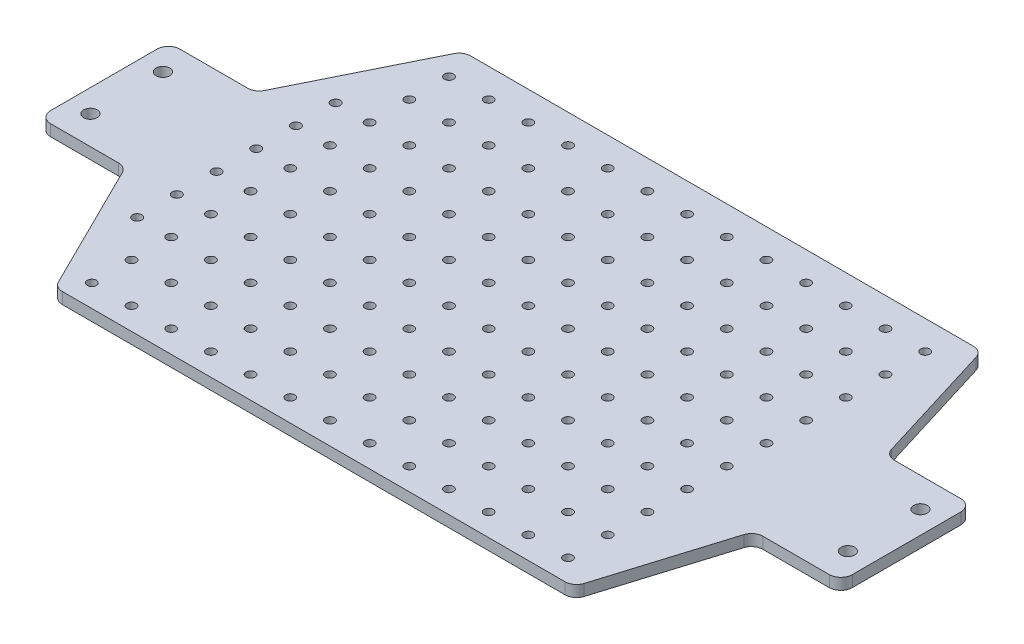
SolidWorks part; units mm, degrees
ref_plane "Front Plane" through (0, 0, 0) normal (0, 0, 1) x (1, 0, 0)
ref_plane "Top Plane" through (0, 0, 0) normal (0, 1, 0) x (1, 0, 0)
ref_plane "Right Plane" through (0, 0, 0) normal (1, 0, 0) x (0, 0, -1)
sketch "Sketch1" plane through (0, 0, 0) normal (0, 1, 0) x (1, 0, 0)
  line L0 (-217.1065, 10.4332) -> (-217.1065, -46.5668)
  line L1 (-217.1065, -46.5668) -> (-179.0065, -46.5668)
  line L2 (-179.0065, -46.5668) -> (-148.5529, -108.0668)
  line L3 (-148.5529, -108.0668) -> (80.0471, -108.0668)
  line L4 (80.0471, -108.0668) -> (98.7935, -47.0668)
  line L5 (98.7935, -47.0668) -> (136.8935, -47.0668)
  line L6 (136.8935, -47.0668) -> (136.8935, 10.9332)
  line L7 (136.8935, 10.9332) -> (98.7935, 10.9332)
  line L8 (98.7935, 10.9332) -> (80.0471, 71.9332)
  line L9 (80.0471, 71.9332) -> (-148.5529, 71.9332)
  line L10 (-148.5529, 71.9332) -> (-179.0065, 10.4332)
  line L11 (-179.0065, 10.4332) -> (-217.1065, 10.4332)
  line L12 (-148.5529, 130.6611) -> (-148.5529, -185.4725) construction
  line L13 (80.0471, 178.7683) -> (80.0471, -185.4725) construction
  dimension "D1" = 228.6
  dimension "D2" = 228.6
  dimension "D3" = 38.1
  dimension "D4" = 38.1
  dimension "D5" = 38.1
  dimension "D6" = 38.1
  dimension "D7" = 58
  dimension "D8" = 57
  dimension "D9" = 180
  dimension "D10" = 354
extrude "Boss-Extrude1" add sketch "Sketch1" along normal blind 5 contours L0 L1 L2 L3 L4 L5 L6 L7 L8 L9 L10 L11
sketch "Sketch2" plane through (0, 5, 0) normal (0, 1, 0) x (1, 0, 0)
  line L0 (-217.1065, 10.4332) -> (-217.1065, -46.5668) construction
  line L5 (-40.0685, 155.1707) -> (-40.0685, -158.002) construction
  line L6 (136.8935, -47.0668) -> (136.8935, 10.9332) construction
  circle A0 centre (-207.1065, -2.0128) radius 3
  circle A1 centre (-207.1065, -34.0128) radius 3
  circle A2 centre (126.9695, -34.0128) radius 3
  circle A3 centre (126.9695, -2.0128) radius 3
  dimension "D1" = 6
  dimension "D4" = 6
  dimension "D2" = 10
  dimension "D3" = 10
  dimension "D5" = 32
  dimension "D6" = 177.038
  dimension "D7" = 9.924
  dimension "D8" = 32
extrude "Cut-Extrude1" cut sketch "Sketch2" against normal blind 5
sketch "Sketch3" plane through (0, 5, 0) normal (0, 1, 0) x (1, 0, 0)
  line L12 (-148.5529, 71.9332) -> (-148.5529, -108.0668) construction
  line L13 (80.0471, 71.9332) -> (80.0471, -108.0668) construction
  circle A0 centre (-142.2029, 59.2332) radius 2
  circle A1 centre (-124.7029, 59.2332) radius 2
  circle A2 centre (-107.2029, 59.2332) radius 2
  circle A3 centre (-89.7029, 59.2332) radius 2
  circle A4 centre (-72.2029, 59.2332) radius 2
  circle A5 centre (-54.7029, 59.2332) radius 2
  circle A6 centre (-37.2029, 59.2332) radius 2
  circle A7 centre (-19.7029, 59.2332) radius 2
  circle A8 centre (-2.2029, 59.2332) radius 2
  circle A9 centre (15.2971, 59.2332) radius 2
  circle A10 centre (32.7971, 59.2332) radius 2
  circle A11 centre (50.2971, 59.2332) radius 2
  circle A12 centre (67.7971, 59.2332) radius 2
  circle A13 centre (-124.7029, 41.7332) radius 2
  circle A14 centre (-107.2029, 41.7332) radius 2
  circle A15 centre (-89.7029, 41.7332) radius 2
  circle A16 centre (-72.2029, 41.7332) radius 2
  circle A17 centre (-54.7029, 41.7332) radius 2
  circle A18 centre (-37.2029, 41.7332) radius 2
  circle A19 centre (-19.7029, 41.7332) radius 2
  circle A20 centre (-2.2029, 41.7332) radius 2
  circle A21 centre (15.2971, 41.7332) radius 2
  circle A22 centre (32.7971, 41.7332) radius 2
  circle A23 centre (50.2971, 41.7332) radius 2
  circle A24 centre (67.7971, 41.7332) radius 2
  circle A25 centre (-124.7029, 24.2332) radius 2
  circle A26 centre (-107.2029, 24.2332) radius 2
  circle A27 centre (-89.7029, 24.2332) radius 2
  circle A28 centre (-72.2029, 24.2332) radius 2
  circle A29 centre (-54.7029, 24.2332) radius 2
  circle A30 centre (-37.2029, 24.2332) radius 2
  circle A31 centre (-19.7029, 24.2332) radius 2
  circle A32 centre (-2.2029, 24.2332) radius 2
  circle A33 centre (15.2971, 24.2332) radius 2
  circle A34 centre (32.7971, 24.2332) radius 2
  circle A35 centre (50.2971, 24.2332) radius 2
  circle A36 centre (67.7971, 24.2332) radius 2
  circle A37 centre (-124.7029, 6.7332) radius 2
  circle A38 centre (-107.2029, 6.7332) radius 2
  circle A39 centre (-89.7029, 6.7332) radius 2
  circle A40 centre (-72.2029, 6.7332) radius 2
  circle A41 centre (-54.7029, 6.7332) radius 2
  circle A42 centre (-37.2029, 6.7332) radius 2
  circle A43 centre (-19.7029, 6.7332) radius 2
  circle A44 centre (-2.2029, 6.7332) radius 2
  circle A45 centre (15.2971, 6.7332) radius 2
  circle A46 centre (32.7971, 6.7332) radius 2
  circle A47 centre (50.2971, 6.7332) radius 2
  circle A48 centre (67.7971, 6.7332) radius 2
  circle A49 centre (-124.7029, -10.7668) radius 2
  circle A50 centre (-107.2029, -10.7668) radius 2
  circle A51 centre (-89.7029, -10.7668) radius 2
  circle A52 centre (-72.2029, -10.7668) radius 2
  circle A53 centre (-54.7029, -10.7668) radius 2
  circle A54 centre (-37.2029, -10.7668) radius 2
  circle A55 centre (-19.7029, -10.7668) radius 2
  circle A56 centre (-2.2029, -10.7668) radius 2
  circle A57 centre (15.2971, -10.7668) radius 2
  circle A58 centre (32.7971, -10.7668) radius 2
  circle A59 centre (50.2971, -10.7668) radius 2
  circle A60 centre (67.7971, -10.7668) radius 2
  circle A61 centre (-124.7029, -28.2668) radius 2
  circle A62 centre (-107.2029, -28.2668) radius 2
  circle A63 centre (-89.7029, -28.2668) radius 2
  circle A64 centre (-72.2029, -28.2668) radius 2
  circle A65 centre (-54.7029, -28.2668) radius 2
  circle A66 centre (-37.2029, -28.2668) radius 2
  circle A67 centre (-19.7029, -28.2668) radius 2
  circle A68 centre (-2.2029, -28.2668) radius 2
  circle A69 centre (15.2971, -28.2668) radius 2
  circle A70 centre (32.7971, -28.2668) radius 2
  circle A71 centre (50.2971, -28.2668) radius 2
  circle A72 centre (67.7971, -28.2668) radius 2
  circle A73 centre (-124.7029, -45.7668) radius 2
  circle A74 centre (-107.2029, -45.7668) radius 2
  circle A75 centre (-89.7029, -45.7668) radius 2
  circle A76 centre (-72.2029, -45.7668) radius 2
  circle A77 centre (-54.7029, -45.7668) radius 2
  circle A78 centre (-37.2029, -45.7668) radius 2
  circle A79 centre (-19.7029, -45.7668) radius 2
  circle A80 centre (-2.2029, -45.7668) radius 2
  circle A81 centre (15.2971, -45.7668) radius 2
  circle A82 centre (32.7971, -45.7668) radius 2
  circle A83 centre (50.2971, -45.7668) radius 2
  circle A84 centre (67.7971, -45.7668) radius 2
  circle A85 centre (-124.7029, -63.2668) radius 2
  circle A86 centre (-107.2029, -63.2668) radius 2
  circle A87 centre (-89.7029, -63.2668) radius 2
  circle A88 centre (-72.2029, -63.2668) radius 2
  circle A89 centre (-54.7029, -63.2668) radius 2
  circle A90 centre (-37.2029, -63.2668) radius 2
  circle A91 centre (-19.7029, -63.2668) radius 2
  circle A92 centre (-2.2029, -63.2668) radius 2
  circle A93 centre (15.2971, -63.2668) radius 2
  circle A94 centre (32.7971, -63.2668) radius 2
  circle A95 centre (50.2971, -63.2668) radius 2
  circle A96 centre (67.7971, -63.2668) radius 2
  circle A97 centre (-124.7029, -80.7668) radius 2
  circle A98 centre (-107.2029, -80.7668) radius 2
  circle A99 centre (-89.7029, -80.7668) radius 2
  circle A100 centre (-72.2029, -80.7668) radius 2
  circle A101 centre (-54.7029, -80.7668) radius 2
  circle A102 centre (-37.2029, -80.7668) radius 2
  circle A103 centre (-19.7029, -80.7668) radius 2
  circle A104 centre (-2.2029, -80.7668) radius 2
  circle A105 centre (15.2971, -80.7668) radius 2
  circle A106 centre (32.7971, -80.7668) radius 2
  circle A107 centre (50.2971, -80.7668) radius 2
  circle A108 centre (67.7971, -80.7668) radius 2
  circle A109 centre (-124.7029, -98.2668) radius 2
  circle A110 centre (-107.2029, -98.2668) radius 2
  circle A111 centre (-89.7029, -98.2668) radius 2
  circle A112 centre (-72.2029, -98.2668) radius 2
  circle A113 centre (-54.7029, -98.2668) radius 2
  circle A114 centre (-37.2029, -98.2668) radius 2
  circle A115 centre (-19.7029, -98.2668) radius 2
  circle A116 centre (-2.2029, -98.2668) radius 2
  circle A117 centre (15.2971, -98.2668) radius 2
  circle A118 centre (32.7971, -98.2668) radius 2
  circle A119 centre (50.2971, -98.2668) radius 2
  circle A120 centre (67.7971, -98.2668) radius 2
  circle A121 centre (-142.2029, 41.7332) radius 2
  circle A122 centre (-142.2029, 24.2332) radius 2
  circle A123 centre (-142.2029, 6.7332) radius 2
  circle A124 centre (-142.2029, -10.7668) radius 2
  circle A125 centre (-142.2029, -28.2668) radius 2
  circle A126 centre (-142.2029, -45.7668) radius 2
  circle A127 centre (-142.2029, -63.2668) radius 2
  circle A128 centre (-142.2029, -80.7668) radius 2
  circle A129 centre (-142.2029, -98.2668) radius 2
  dimension "D4" = 4
  dimension "D5" = 13
  dimension "D6" = 10
extrude "Cut-Extrude4" cut sketch "Sketch3" against normal blind 5
fillet "Fillet1" radius 5.08 12 edges at (-148.5529, 2.5, -71.9332) (80.0471, 2.5, -71.9332) (98.7935, 2.5, -10.9332) (136.8935, 2.5, -10.9332) (136.8935, 2.5, 47.0668) (98.7935, 2.5, 47.0668) (80.0471, 2.5, 108.0668) (-148.5529, 2.5, 108.0668) (-217.1065, 2.5, 46.5668) (-217.1065, 2.5, -10.4332) (-179.0065, 2.5, -10.4332) (-179.0065, 2.5, 46.5668)
sketch "Sketch4" plane through (0, 5, 0) normal (0, 1, 0) x (1, 0, 0)
  line L0 (-142.2029, 41.7332) -> (-157.2029, 41.7332) construction
  line L1 (-157.2029, 41.7332) -> (-157.2029, -82.0749) construction
  line L2 (-142.2029, 24.2332) -> (-165.3424, 24.2332) construction
  line L3 (-142.2029, 6.7332) -> (-165.3424, 6.7332) construction
  line L4 (-142.2029, -10.7668) -> (-164.401, -10.7668) construction
  line L5 (-142.2029, -28.2668) -> (-164.0845, -28.2668) construction
  line L6 (-142.2029, -45.7668) -> (-162.9833, -45.7668) construction
  line L7 (-142.2029, -63.2668) -> (-165.9815, -63.2668) construction
  line L8 (-142.2029, -80.7668) -> (-164.401, -80.7668) construction
  circle A1 centre (-157.2029, 24.2332) radius 2.032
  circle A2 centre (-157.2029, 6.7332) radius 2.032
  circle A3 centre (-157.2029, -10.7668) radius 2.032
  circle A4 centre (-157.2029, -28.2668) radius 2.032
  circle A5 centre (-157.2029, -45.7668) radius 2.032
  circle A6 centre (-157.2029, -63.2668) radius 2.032
  point P31 (-157.2029, -80.7668)
  dimension "D1" = 15
extrude "Cut-Extrude5" cut sketch "Sketch4" against normal blind 5
sketch "Sketch6" plane through (0, 0, 0) normal (0, -1, 0) x (-1, 0, 0)
sketch "Sketch7" plane through (0, 5, 0) normal (0, 1, 0) x (1, 0, 0)
  line L0 (-40.0685, 111.8606) -> (-40.0685, -155.0621) construction
  line L1 (-217.1065, 5.3532) -> (-217.1065, -41.4868) construction
  line L2 (136.8935, -41.9868) -> (136.8935, 5.8532) construction
  dimension "D1" = 354
  dimension "D2" = 177.038
